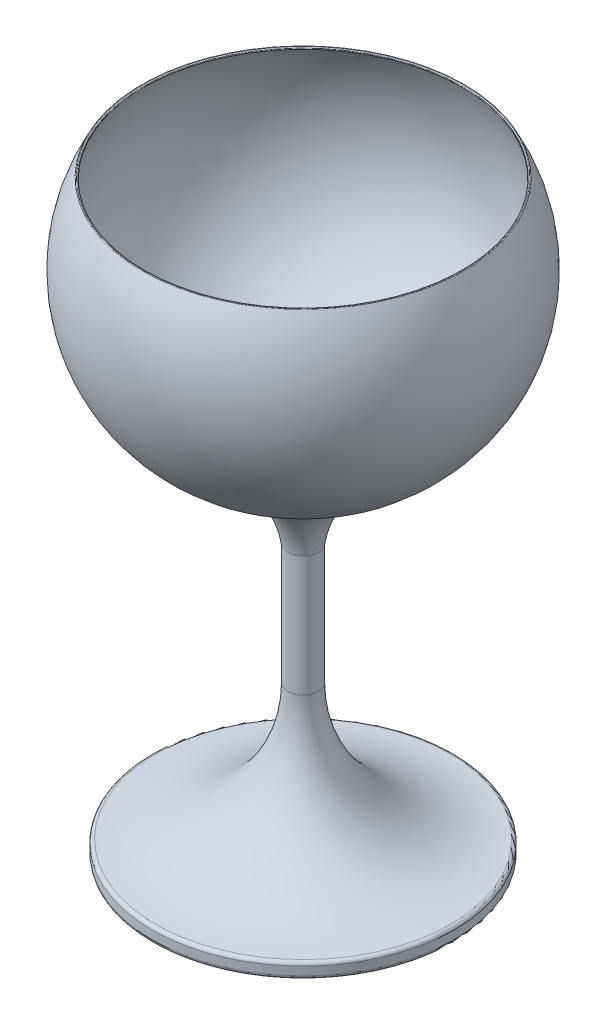
SolidWorks part; units mm, degrees
ref_plane "Front Plane" through (0, 0, 0) normal (0, 0, 1) x (1, 0, 0)
ref_plane "Top Plane" through (0, 0, 0) normal (0, 1, 0) x (1, 0, 0)
ref_plane "Right Plane" through (0, 0, 0) normal (1, 0, 0) x (0, 0, -1)
sketch "Sketch1" plane through (0, 0, 0) normal (0, 0, 1) x (1, 0, 0)
  line L0 (0, -162.5703) -> (0, 98.1106) construction
  line L1 (4.5, -112.9127) -> (4.5, -77.4005)
  line L2 (19.5466, -54.1909) -> (23.7533, -52.2929)
  line L3 (21.9087, -53.9479) -> (24.0617, -52.9766)
  line L4 (44.5, -153.9005) -> (44.5, -156.4005)
  line L5 (43.5, -157.4005) -> (33.0309, -157.4005)
  line L6 (21.6003, -53.2643) -> (23.7533, -52.2929) construction
  line L7 (47.0156, 16.085) -> (47.3236, 16.2512)
  line L8 (0, -57.6865) -> (0, -153.4005)
  arc A0 (4.5, -77.4005) -> (21.9087, -53.9479) centre (34.2463, -81.2936) cw
  arc A1 (0, -57.6865) -> (18.4848, -54.5334) centre (-41.1788, 239.4739) ccw
  arc A2 (4.5, -112.9127) -> (43.5244, -152.9008) centre (44.5, -112.9127) ccw
  arc A4 (44.5, -153.9005) -> (43.5244, -152.9008) centre (43.5, -153.9005) ccw
  arc A6 (24.0617, -52.9766) -> (47.595, 16.1695) centre (3.499, -7.4005) ccw
  arc A7 (18.4848, -54.5334) -> (19.5466, -54.1909) centre (17.4904, -49.6332) ccw
  arc A8 (32.0284, -157.299) -> (33.0309, -157.4005) centre (33.0309, -152.4005) ccw
  arc A9 (32.0284, -157.299) -> (0, -153.4005) centre (-8.0725, -353.2375) ccw
  arc A10 (44.5, -156.4005) -> (43.5, -157.4005) centre (43.5, -156.4005) cw
  arc A11 (23.7533, -52.2929) -> (46.9342, 15.8147) centre (3.499, -7.4005) ccw
  arc A12 (24.0617, -52.9766) -> (47.5, 16.3464) centre (3.499, -7.4005) ccw construction
  arc A13 (47.595, 16.1695) -> (47.3236, 16.2512) centre (47.4186, 16.0752) ccw
  arc A14 (23.7533, -52.2929) -> (46.84, 15.9902) centre (3.499, -7.4005) ccw construction
  arc A15 (46.9342, 15.8147) -> (47.0156, 16.085) centre (47.1106, 15.909) cw
  point P5 (4.5, -95.1566)
  point P20 (44.5, -152.9127)
  point P32 (44.5, -157.4005)
  point P39 (47.5, 16.3464)
  dimension "D3" = 40
  dimension "D4" = 300
  dimension "D5" = 30
  dimension "D7" = 1
  dimension "D11" = 100
  dimension "D9" = 10
  dimension "D13" = 5
  dimension "D17" = 200
  dimension "D18" = 1
  dimension "D15" = 0.2
  dimension "D1" = 4.5
  dimension "D8" = 3.5
  dimension "D10" = 80
  dimension "D12" = 150
  dimension "D14" = 47.5
  dimension "D16" = 4
  dimension "D2" = 0.75
revolve "Revolve1" add sketch "Sketch1" angle 360 about L0
